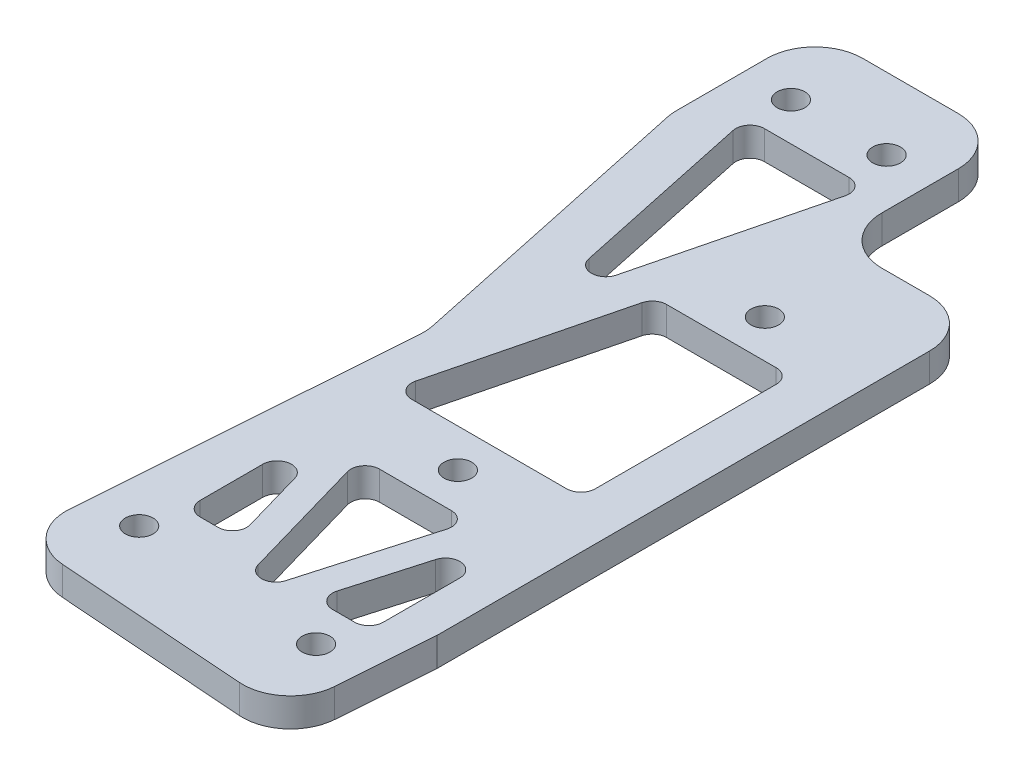
SolidWorks part; units mm, degrees
material "Thornel Mat VMA"
ref_plane "前视基准面" through (0, 0, 0) normal (0, 0, 1) x (1, 0, 0)
ref_plane "上视基准面" through (0, 0, 0) normal (0, 1, 0) x (1, 0, 0)
ref_plane "右视基准面" through (0, 0, 0) normal (1, 0, 0) x (0, 0, -1)
other "Configuration Table"
sketch "草图1" plane through (0, 0, 0) normal (0, 1, 0) x (1, 0, 0)
  line L0 (0, -10) -> (-1.0892, -24.9604) construction
  line L1 (0, 0) -> (680, 0) construction
  line L2 (0, 0) -> (0, 15) construction
  line L3 (0, 15) -> (680, 15) construction
  line L4 (680, 0) -> (680, 15) construction
  line L5 (0, -10) -> (680, -59.51) construction
  line L6 (-1.0892, -24.9604) -> (678.9108, -74.4704) construction
  line L7 (680, -59.51) -> (678.9108, -74.4704) construction
  line L8 (0, 0) -> (0, -10) construction
  line L9 (0, -10) -> (19.9472, -11.4523) construction
  line L10 (19.9472, -11.4523) -> (20.781, 0) construction
  line L11 (20.781, 0) -> (0, 0) construction
  line L12 (654.2534, 0) -> (650.0792, -57.3315) construction
  line L13 (650.0792, -57.3315) -> (680, -59.51) construction
  line L14 (680, -59.51) -> (680, 0) construction
  line L15 (680, 0) -> (654.2534, 0) construction
  line L16 (570.2904, -51.5222) -> (571.6245, -33.1995) construction
  line L17 (570.2904, -51.5222) -> (-45.7125, -51.5222) construction
  line L19 (645, 15) -> (680, 15) construction
  line L20 (680, 15) -> (680, 0) construction
  line L21 (650.0792, -57.3315) -> (648.99, -72.2919)
  line L22 (584.997, 7.5) -> (717.5964, 7.5) construction
  line L23 (705.0943, -68.8569) -> (547.6511, -57.3937) construction
  line L24 (665.0396, -58.4207) -> (668.4845, -11.1068) construction
  line L25 (648.99, -72.2919) -> (678.9108, -74.4704)
  line L26 (680, -59.51) -> (678.9108, -74.4704)
  line L27 (19.9472, -11.4523) -> (19.9472, -68.8569) construction
  line L28 (654.2534, 0) -> (645, 0) construction
  line L29 (645, 0) -> (645, 15)
  line L30 (680, -59.51) -> (680, -3)
  line L31 (680, -3) -> (665, -3)
  line L32 (665, -3) -> (665, 15)
  line L33 (665, 15) -> (645, 15)
  line L34 (645, 0) -> (651.8946, -32.3975)
  line L35 (651.8946, -32.3975) -> (650.0792, -57.3315)
  circle A0 centre (660, 7.5) radius 1.45
  circle A1 centre (650, 7.5) radius 1.45
  circle A2 centre (654.5214, -65.1748) radius 1.45
  circle A3 centre (674.4686, -66.6271) radius 1.45
  circle A4 centre (666.1289, -43.4604) radius 1.45
  circle A5 centre (668.3073, -13.5396) radius 1.45
  dimension "D11" = 2.9
  dimension "D12" = 15
  dimension "D13" = 30
  dimension "D15" = 20
  dimension "D16" = 5
  dimension "D17" = 5
  dimension "D18" = 5
  dimension "D19" = 10
  dimension "D21" = 5
  dimension "D1" = 15
  dimension "D2" = 15
  dimension "D3" = 680
  dimension "D4" = 20
  dimension "D5" = 80
  dimension "D6" = 681.8
  dimension "D7" = 30
  dimension "D8" = 10
  dimension "D9" = 7.5
  dimension "D10" = 7.5
  dimension "D14" = 15
  dimension "D20" = 3
  dimension "D22" = 25
extrude "凸台-拉伸1" add sketch "草图1" along normal blind 3
fillet "圆角1" radius 5 8 edges at (678.9108, 1.5, 74.4704) (665, 1.5, -15) (680, 1.5, 3) (645, 1.5, -15) (665, 1.5, 3) (648.99, 1.5, 72.2919) (651.8946, 1.5, 32.3975) (645, 1.5, 0)
sketch "草图2" plane through (0, 3, 0) normal (0, 1, 0) x (1, 0, 0)
  line L0 (649.3671, 3.5) -> (655.1784, -23.807)
  line L1 (655.1784, -23.807) -> (662, 3.5)
  line L2 (662, 3.5) -> (649.3671, 3.5)
  line L3 (660.867, -17.5396) -> (675, -17.5396)
  line L4 (675, -17.5396) -> (675, -39.4604)
  line L5 (675, -39.4604) -> (655.391, -39.4604)
  line L6 (655.391, -39.4604) -> (660.867, -17.5396)
  line L7 (659.9469, -47.4604) -> (671.4441, -47.4604)
  line L8 (671.4441, -47.4604) -> (665.6955, -67.4923)
  line L9 (665.6955, -67.4923) -> (659.9469, -47.4604)
  line L10 (645.1095, -0.5146) -> (651.7467, -31.7024) construction
  line L11 (653.9768, -72.655) -> (673.924, -74.1073) construction
  line L13 (680, -59.51) -> (680, -8) construction
  line L14 (665, 2) -> (665, 10) construction
  line L15 (651.843, -33.1063) -> (649.353, -67.3051) construction
  line L16 (655.391, -42.4604) -> (655.391, -61.1748)
  line L17 (655.391, -61.1748) -> (660.7615, -61.1748)
  line L18 (660.7615, -61.1748) -> (655.391, -42.4604)
  line L19 (676, -42.4604) -> (670.2127, -62.6271)
  line L20 (670.2127, -62.6271) -> (676, -62.6271)
  line L21 (676, -62.6271) -> (676, -42.4604)
  circle A0 centre (666.1289, -43.4604) radius 1.45 construction
  circle A1 centre (668.3073, -13.5396) radius 1.45 construction
  circle A2 centre (650, 7.5) radius 1.45 construction
  circle A3 centre (654.5214, -65.1748) radius 1.45 construction
  circle A4 centre (674.4686, -66.6271) radius 1.45 construction
  dimension "D5" = 4
  dimension "D1" = 4
  dimension "D2" = 4
  dimension "D3" = 4
  dimension "D4" = 5
  dimension "D6" = 4
  dimension "D7" = 5
  dimension "D8" = 3
  dimension "D9" = 4
  dimension "D10" = 4
  dimension "D11" = 4
  dimension "D12" = 4
  dimension "D13" = 3
  dimension "D14" = 3
  dimension "D15" = 6
  dimension "D16" = 3
extrude "切除-拉伸1" cut sketch "草图2" against normal through all
fillet "圆角2" radius 1.5 17 edges at (680, 1.5, 59.51) (655.1784, 1.5, 23.807) (662, 1.5, -3.5) (655.391, 1.5, 61.1748) (655.391, 1.5, 42.4604) (660.7615, 1.5, 61.1748) (670.2127, 1.5, 62.6271) (676, 1.5, 42.4604) (676, 1.5, 62.6271) (671.4441, 1.5, 47.4604) (665.6955, 1.5, 67.4923) (659.9469, 1.5, 47.4604) (675, 1.5, 17.5396) (675, 1.5, 39.4604) (655.391, 1.5, 39.4604) (660.867, 1.5, 17.5396) (649.3671, 1.5, -3.5)
